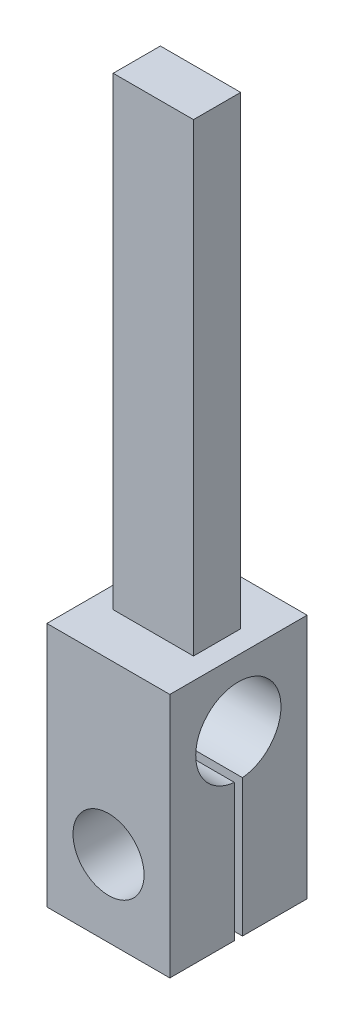
SolidWorks part; units mm, degrees
ref_plane "Front Plane" through (0, 0, 0) normal (0, 0, 1) x (1, 0, 0)
ref_plane "Top Plane" through (0, 0, 0) normal (0, 1, 0) x (1, 0, 0)
ref_plane "Right Plane" through (0, 0, 0) normal (1, 0, 0) x (0, 0, -1)
sketch "Sketch1" plane through (0, 0, 0) normal (1, 0, 0) x (0, 0, -1)
  line L0 (1.5561, -9.9154) -> (3.9165, -9.9163)
  line L1 (1.5561, -0.9285) -> (1.5561, -9.9154)
  line L2 (6.5797, -9.9174) -> (6.5797, -0.9285)
  line L3 (4.2148, -9.9164) -> (6.5797, -9.9174)
  line L8 (1.5561, -0.9285) -> (6.5797, -0.9285)
  line L9 (3.9165, -4.8956) -> (3.9165, -9.9163)
  line L11 (4.2148, -4.895) -> (4.2148, -9.9164)
  arc A1 (4.2148, -4.895) -> (3.9165, -4.8956) centre (4.0628, -3.3424) ccw
  point P2 (3.9165, -4.8956)
  point P3 (4.2148, -4.895)
extrude "Boss-Extrude2" add sketch "Sketch1" along normal blind 4.5
sketch "Sketch3" plane through (0, 0, -1.5561) normal (0, 0, 1) x (1, 0, 0)
  circle A0 centre (2.256, -7.1217) radius 1.3
  circle A1 centre (2.256, -7.1217) radius 1.3
extrude "Cut-Extrude1" cut sketch "Sketch3" against normal blind 10.5 contours A0
sketch "Sketch6" plane through (0, -0.9285, 0) normal (0, 1, 0) x (1, 0, 0)
  line L0 (0, 4.0679) -> (4.5, 4.0679) construction
  line L1 (0, 6.5797) -> (0, 1.5561) construction
  line L2 (4.5, 6.5797) -> (4.5, 1.5561) construction
  line L4 (0.7779, 4.9314) -> (3.7164, 4.9314)
  line L7 (0.7779, 3.2044) -> (3.7164, 3.2044)
  line L9 (0.7779, 4.9314) -> (0.7779, 3.2044)
  line L10 (3.7164, 3.2044) -> (3.7164, 4.9314)
extrude "Boss-Extrude5" add sketch "Sketch6" along normal blind 17
sketch "Sketch4" plane through (0, -0.9285, 0) normal (0, 1, 0) x (1, 0, 0)
  line L1 (0.5793, 4.9421) -> (4.0691, 4.9421)
  line L2 (0.5793, 4.9421) -> (0.5793, 3.2283)
  line L3 (0.5793, 3.2283) -> (4.0691, 3.2283)
  line L4 (4.0691, 4.9421) -> (4.0691, 3.2283)
